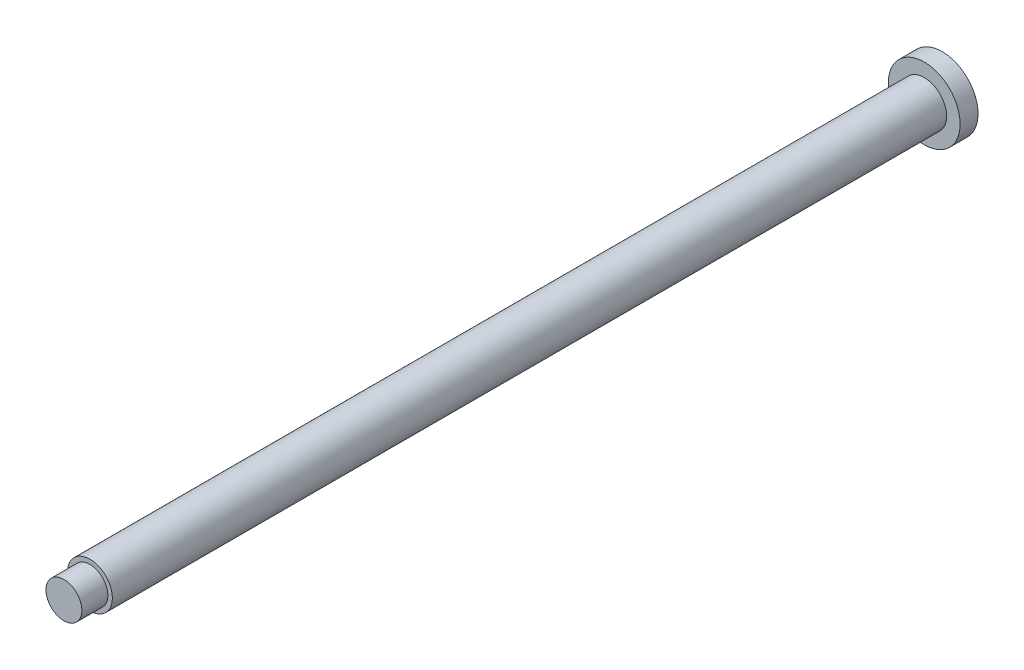
SolidWorks part; units mm, degrees
ref_plane "Front Plane" through (0, 0, 0) normal (1, 0, 0) x (0, 1, 0)
ref_plane "Top Plane" through (0, 0, 0) normal (0, 0, 1) x (0, 1, 0)
ref_plane "Right Plane" through (0, 0, 0) normal (0, 1, 0) x (-1, 0, 0)
sketch "Sketch1" plane through (0, 0, 0) normal (0, 0, 1) x (0, 1, 0)
  circle A0 centre (0, 0) radius 2.5
extrude "Boss-Extrude1" add sketch "Sketch1" along normal blind 93 contours A0
sketch "Sketch2" plane through (0, 0, 0) normal (0, 0, -1) x (1, 0, 0)
  circle A0 centre (0, 0) radius 4
extrude "Boss-Extrude2" add sketch "Sketch2" along normal blind 2
sketch "Sketch3" plane through (0, 0, -2) normal (0, 0, -1) x (1, 0, 0)
  circle A0 centre (0, 0) radius 2.05
extrude "Cut-Extrude1" cut sketch "Sketch3" against normal blind 3
sketch "Sketch4" plane through (0, 0, 93) normal (0, 0, 1) x (1, 0, 0)
  circle A0 centre (0, 0) radius 2
extrude "Boss-Extrude3" add sketch "Sketch4" along normal blind 2.9
